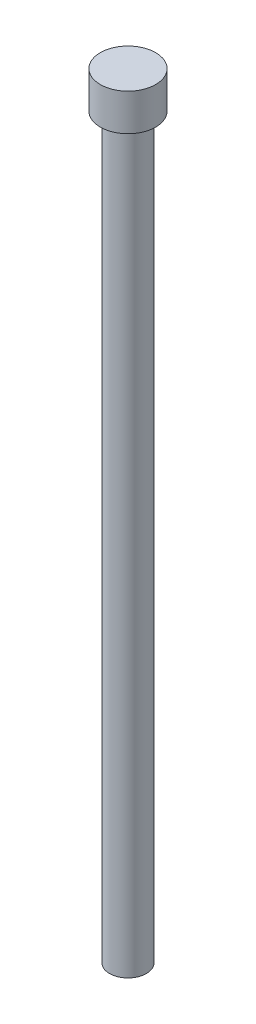
SolidWorks part; units mm, degrees
ref_plane "Front Plane" through (0, 0, 0) normal (0, 0, 1) x (1, 0, 0)
ref_plane "Top Plane" through (0, 0, 0) normal (0, 1, 0) x (1, 0, 0)
ref_plane "Right Plane" through (0, 0, 0) normal (1, 0, 0) x (0, 0, -1)
sketch "Sketch1" plane through (0, 0, 0) normal (0, 1, 0) x (1, 0, 0)
  circle A0 centre (0, 0) radius 4.7625
  dimension "D1" = 9.525
extrude "Boss-Extrude1" add sketch "Sketch1" along normal blind 6.35
sketch "Sketch2" plane through (0, 0, 0) normal (0, -1, 0) x (1, 0, 0)
  circle A0 centre (0, 0) radius 3.175
  dimension "D1" = 6.35
extrude "Boss-Extrude2" add sketch "Sketch2" along normal blind 127
